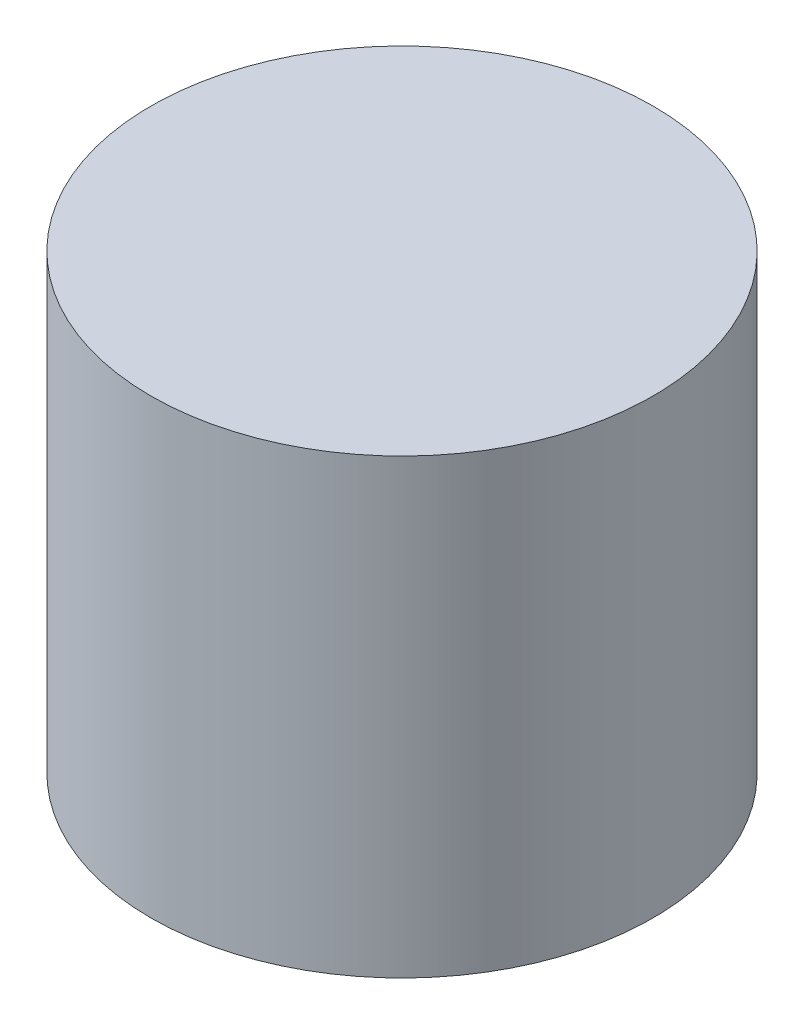
SolidWorks part; units mm, degrees
ref_plane "Plano frontal" through (0, 0, 0) normal (0, 0, 1) x (1, 0, 0)
ref_plane "Plano superior" through (0, 0, 0) normal (0, 1, 0) x (1, 0, 0)
ref_plane "Plano direito" through (0, 0, 0) normal (1, 0, 0) x (0, 0, -1)
sketch "Esboço1" plane through (0, 0, 0) normal (0, 0, 1) x (1, 0, 0)
  line L0 (0, 0) -> (0, 36) construction
  line L1 (0, 0) -> (20, 0)
  line L2 (20, 0) -> (20, 36)
  line L3 (20, 36) -> (0, 36)
  line L4 (0, 0) -> (0, 36)
  dimension "D1" = 20
  dimension "D2" = 36
revolve "Revolução1" add sketch "Esboço1" angle 360 about L0
